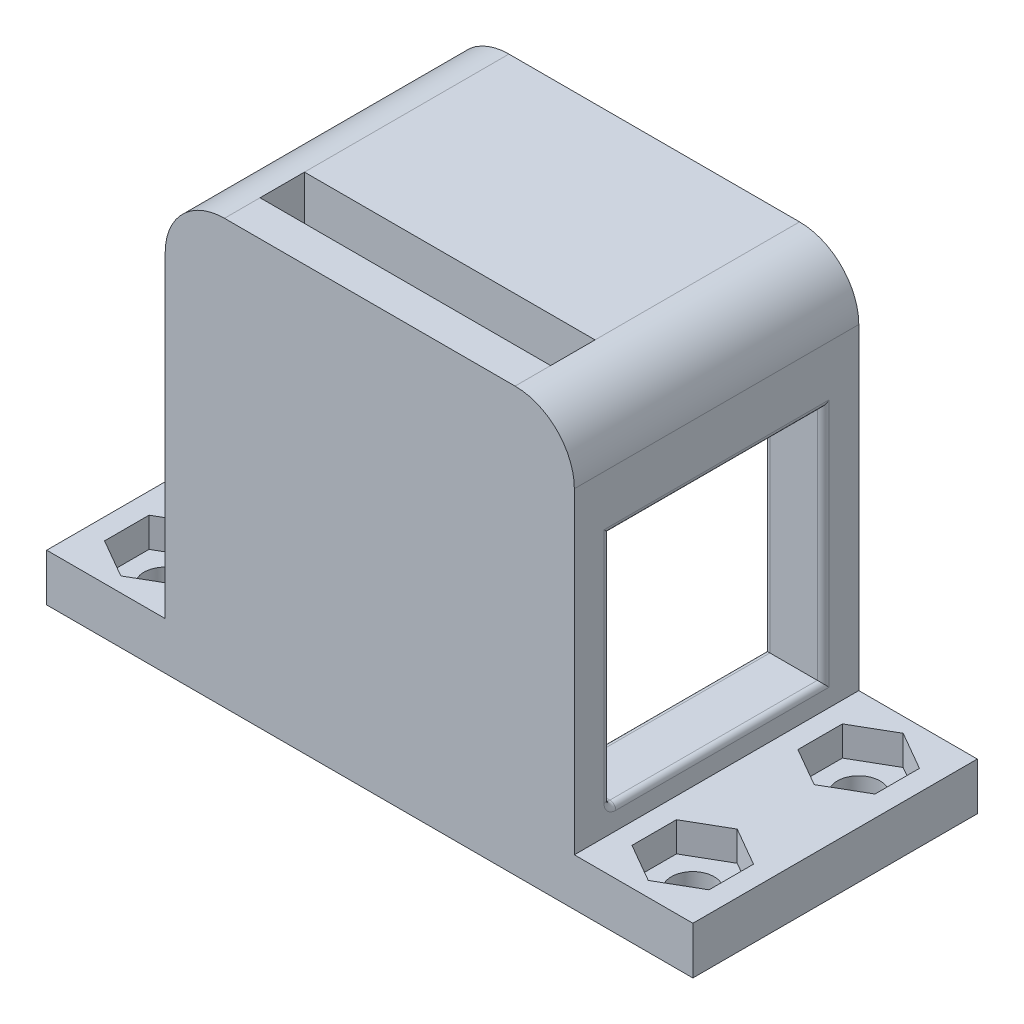
SolidWorks part; units mm, degrees
ref_plane "Front Plane" through (0, 0, 0) normal (0, 0, 1) x (1, 0, 0)
ref_plane "Top Plane" through (0, 0, 0) normal (0, 1, 0) x (1, 0, 0)
ref_plane "Right Plane" through (0, 0, 0) normal (1, 0, 0) x (0, 0, -1)
sketch "Sketch1" plane through (0, 0, 0) normal (0, 0, 1) x (1, 0, 0)
  line L1 (-27.2601, 5.3) -> (-12.2601, 5.3)
  line L2 (-27.2601, 5.3) -> (-27.2601, 9.3)
  line L3 (-27.2601, 9.3) -> (-17.2601, 9.3)
  line L6 (-12.2601, 5.3) -> (-12.2601, 36.5)
  line L8 (-17.2601, 9.3) -> (-17.2601, 39.5587)
  line L9 (-12, 41.05) -> (12, 41.05)
  line L11 (-12.2601, 36.5) -> (12.2601, 36.5)
  line L14 (17.2601, 9.3) -> (17.2601, 38.8587)
  line L15 (12, 41.05) -> (15.1507, 41.05)
  line L16 (12.2601, 5.3) -> (12.2601, 36.5)
  line L18 (27.2601, 9.3) -> (17.2601, 9.3)
  line L19 (27.2601, 5.3) -> (27.2601, 9.3)
  line L20 (27.2601, 5.3) -> (12.2601, 5.3)
  line L21 (-17.2601, 39.5587) -> (-17.2601, 41.05)
  line L22 (-17.2601, 41.05) -> (-12, 41.05)
  line L23 (15.1507, 41.05) -> (17.2601, 41.05)
  line L25 (17.2601, 41.05) -> (17.2601, 38.8587)
  point P4 (0, 36.5)
  dimension "D2" = 5
  dimension "D3" = 10
  dimension "D6" = 4.55
  dimension "D8" = 24.5203
  dimension "D9" = 31.2
  dimension "D10" = 4
  dimension "D11" = 4
extrude "Boss-Extrude1" add sketch "Sketch1" along normal blind 17.5
sketch "Sketch2" plane through (0, 0, 17.5) normal (0, 0, 1) x (1, 0, 0)
  line L0 (-17.2601, 9.3) -> (-17.2601, 41.05)
  line L1 (-17.2601, 41.05) -> (17.2601, 41.05)
  line L2 (17.2601, 41.05) -> (17.2601, 5.3)
  line L3 (12.2601, 5.3) -> (27.2601, 5.3) construction
  line L4 (17.2601, 5.3) -> (-17.2601, 5.3)
  line L5 (-27.2601, 5.3) -> (-12.2601, 5.3) construction
  line L6 (-17.2601, 5.3) -> (-17.2601, 9.3)
extrude "Boss-Extrude2" add sketch "Sketch2" along normal blind 6.5
sketch "Sketch4" plane through (0, 0, 17.5) normal (0, 0, -1) x (-1, 0, 0)
  line L1 (-12.2601, 36.5) -> (12.2601, 36.5)
  line L2 (-12.2601, 36.5) -> (-12.2601, 5.3)
  line L3 (-12.2601, 5.3) -> (12.2601, 5.3)
  line L4 (12.2601, 36.5) -> (12.2601, 5.3)
extrude "Cut-Extrude1" cut sketch "Sketch4" against normal blind 3.5
sketch "Sketch5" plane through (0, 0, 21) normal (0, 0, -1) x (-1, 0, 0)
  line L0 (-17.2601, 41.05) -> (17.2601, 41.05) construction
  line L1 (-12.2601, 36.5) -> (-14.9466, 36.5)
  line L2 (-12.2601, 36.5) -> (-12.2601, 38.5)
  line L3 (-12.2601, 38.5) -> (-14.9466, 38.5)
  line L4 (-14.9466, 36.5) -> (-14.9466, 38.5)
  dimension "D1" = 2.55
extrude "Cut-Extrude2" [suppressed] cut sketch "Sketch5" along normal blind 4.5
fillet "Fillet1" radius 5 2 edges at (-17.2601, 41.05, 12) (17.2601, 41.05, 12)
sketch "Sketch7" plane through (0, 0, 17.5) normal (0, 0, 1) x (1, 0, 0)
  line L1 (-27.2601, 9.3) -> (-17.2601, 9.3)
  line L2 (-27.2601, 9.3) -> (-27.2601, 5.3)
  line L3 (-27.2601, 5.3) -> (-17.2601, 5.3)
  line L4 (-17.2601, 9.3) -> (-17.2601, 5.3)
  line L5 (17.2601, 9.3) -> (27.2601, 9.3)
  line L6 (17.2601, 9.3) -> (17.2601, 5.3)
  line L7 (17.2601, 5.3) -> (27.2601, 5.3)
  line L8 (27.2601, 9.3) -> (27.2601, 5.3)
extrude "Boss-Extrude3" add sketch "Sketch7" along normal through all
sketch "Sketch6" plane through (0, 9.3, 0) normal (0, 1, 0) x (1, 0, 0)
  line L0 (27.2601, -24) -> (27.2601, 0) construction
  line L40 (22.25, -1.2472) -> (25.5, -3.1236)
  line L45 (92.1046, -12) -> (-37.5844, -12) construction
  line L47 (19, -3.1236) -> (22.25, -1.2472)
  line L48 (19, -6.8764) -> (19, -3.1236)
  line L49 (22.25, -8.7528) -> (19, -6.8764)
  line L56 (25.5, -6.8764) -> (22.25, -8.7528)
  line L65 (25.5, -3.1236) -> (25.5, -6.8764)
  line L66 (22.25, -22.7528) -> (25.5, -20.8764)
  line L67 (25.5, -20.8764) -> (25.5, -17.1236)
  line L68 (25.5, -17.1236) -> (22.25, -15.2472)
  line L69 (22.25, -15.2472) -> (19, -17.1236)
  line L70 (19, -17.1236) -> (19, -20.8764)
  line L71 (19, -20.8764) -> (22.25, -22.7528)
  line L72 (0, -59.0369) -> (0, -80.7994) construction
  line L74 (0, -55) -> (0, 55) construction
  line L75 (-22.25, -8.7528) -> (-19, -6.8764)
  line L76 (-19, -6.8764) -> (-19, -3.1236)
  line L77 (-19, -3.1236) -> (-22.25, -1.2472)
  line L78 (-22.25, -1.2472) -> (-25.5, -3.1236)
  line L79 (-25.5, -3.1236) -> (-25.5, -6.8764)
  line L80 (-25.5, -6.8764) -> (-22.25, -8.7528)
  line L81 (-22.25, -15.2472) -> (-19, -17.1236)
  line L82 (-19, -17.1236) -> (-19, -20.8764)
  line L83 (-19, -20.8764) -> (-22.25, -22.7528)
  line L84 (-22.25, -22.7528) -> (-25.5, -20.8764)
  line L85 (-25.5, -20.8764) -> (-25.5, -17.1236)
  line L86 (-25.5, -17.1236) -> (-22.25, -15.2472)
  circle A4 centre (22.25, -19) radius 3.25 construction
  point P4 (27.2601, -12)
  point P12 (20.625, -16.1854)
  point P34 (-20.625, -16.1854)
  dimension "D1" = 22.25
  dimension "D4" = 6.5
  dimension "D2" = 7
fillet "Fillet2" radius 1 2 edges at (12.2601, 20.9, 0) (-12.2601, 20.9, 0)
sketch "Sketch8" plane through (-17.2601, 0, 0) normal (-1, 0, 0) x (0, 0, 1)
  line L0 (24, 36.05) -> (24, 9.3) construction
  line L1 (3, 31.3) -> (21, 31.3)
  line L2 (3, 31.3) -> (3, 11.3)
  line L3 (3, 11.3) -> (21, 11.3)
  line L4 (21, 31.3) -> (21, 11.3)
  line L6 (24, 9.3) -> (0, 9.3) construction
  dimension "D1" = 18
  dimension "D2" = 20
  dimension "D3" = 3
  dimension "D4" = 2
extrude "Cut-Extrude4" cut sketch "Sketch8" against normal through all
fillet "Fillet3" radius 0.5 16 edges at (-14.7601, 11.3, 21) (-17.2601, 11.3, 12) (-17.2601, 21.3, 3) (-17.2601, 21.3, 21) (-17.2601, 31.3, 12) (-12.2601, 11.3, 12) (-12.2601, 21.3, 3) (-12.2601, 8.3, 21) (12.2601, 8.3, 21) (17.2601, 11.3, 12) (12.2601, 21.3, 3) (12.2601, 11.3, 12) (17.2601, 31.3, 12) (17.2601, 21.3, 3) (17.2601, 21.3, 21) (14.7601, 11.3, 21)
extrude "Cut-Extrude7" cut sketch "Sketch6" against normal offset from surface (2.5 mm away) 1.5 up to face at (0, 5.3, 11.0661)
sketch "Sketch11" plane through (0, 9.3, 0) normal (0, 1, 0) x (1, 0, 0)
  line L0 (22.25, -22.7528) -> (25.5, -20.8764) construction
  line L1 (25.5, -17.1236) -> (22.25, -15.2472) construction
  line L2 (19, -17.1236) -> (19, -20.8764) construction
  line L3 (22.25, -8.7528) -> (25.5, -6.8764) construction
  line L4 (25.5, -3.1236) -> (22.25, -1.2472) construction
  line L5 (19, -3.1236) -> (19, -6.8764) construction
  line L6 (-22.25, -22.7528) -> (-19, -20.8764) construction
  line L7 (-25.5, -17.1236) -> (-25.5, -20.8764) construction
  line L8 (-19, -17.1236) -> (-22.25, -15.2472) construction
  line L9 (-22.25, -8.7528) -> (-19, -6.8764) construction
  line L10 (-19, -3.1236) -> (-22.25, -1.2472) construction
  line L11 (-25.5, -3.1236) -> (-25.5, -6.8764) construction
  circle A0 centre (22.25, -19) radius 3.25
  circle A1 centre (22.25, -5) radius 3.25
  circle A2 centre (-22.25, -5) radius 3.25
  circle A3 centre (-22.25, -19) radius 3.25
hole_wizard "M3 Clearance Hole1" positions "Sketch12" profile "Sketch13" hole size "M3" standard "ANSI Metric" end condition through all
sketch "Sketch12" plane through (0, 9.3, 0) normal (0, 1, 0) x (1, 0, 0)
  point P0 (22.25, -19)
  point P3 (22.25, -5)
  point P6 (-22.25, -5)
  point P9 (-22.25, -19)
sketch "Sketch13" plane through (22.25, 9.3, 19) normal (1, 0, 0) x (0, 0, 1)
  line L0 (0, 0) -> (0, 4)
  line L1 (0, 4) -> (1.8, 4)
  line L2 (1.8, 4) -> (1.8, 0)
  line L5 (1.8, 0) -> (0, 0)
  line L11 (0, -6.35) -> (0, 107.95) construction
  dimension "Thru Hole Dia." = 3.6
  dimension "Thru Hole Depth" = 4
sketch "Sketch14" plane through (0, 36.5, 0) normal (0, -1, 0) x (1, 0, 0)
  line L0 (-12.2601, 21) -> (12.2601, 21) construction
  line L1 (12.2601, 17.25) -> (-12.2601, 17.25)
  line L2 (12.2601, 17.25) -> (12.2601, 21)
  line L3 (12.2601, 21) -> (-12.2601, 21)
  line L4 (-12.2601, 17.25) -> (-12.2601, 21)
  line L5 (-12.2601, 21) -> (-12.2601, 1) construction
  line L6 (12.2601, 21) -> (12.2601, 1) construction
  dimension "D1" = 3.75
extrude "Cut-Extrude8" cut sketch "Sketch14" against normal through all
